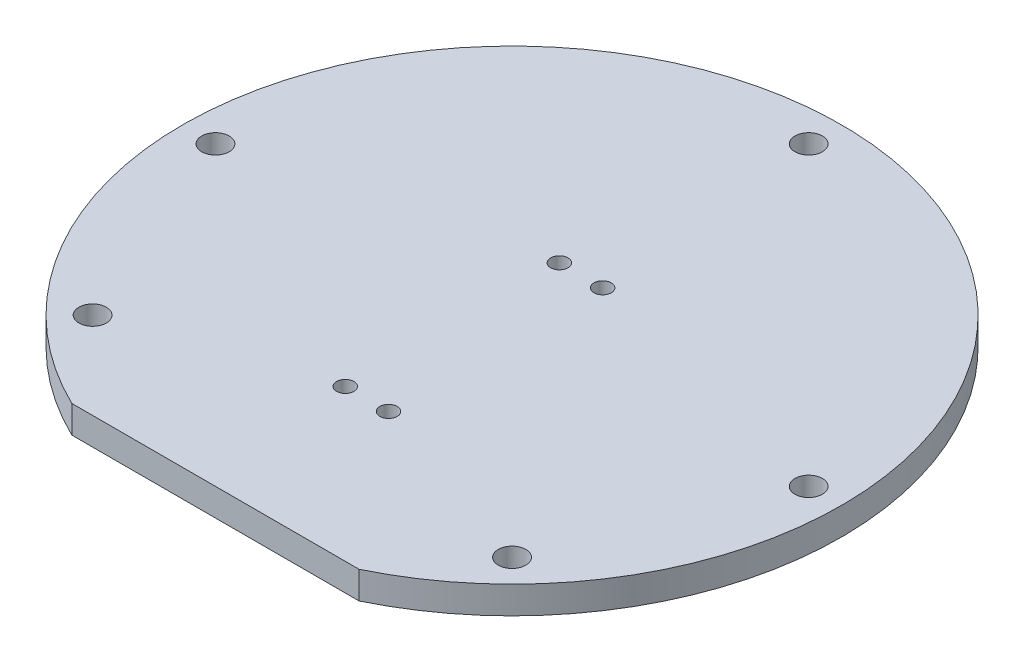
SolidWorks part; units mm, degrees
ref_plane "Front" through (0, 0, 0) normal (0, 0, 1) x (1, 0, 0)
ref_plane "Top" through (0, 0, 0) normal (0, 1, 0) x (1, 0, 0)
ref_plane "Right" through (0, 0, 0) normal (1, 0, 0) x (0, 0, -1)
sketch "Sketch1" plane through (0, 0, 0) normal (0, 1, 0) x (1, 0, 0)
  line L0 (-5.0038, 15.9411) -> (5.0038, -33.5635) construction
  line L1 (-5.0038, -33.5635) -> (5.0038, 15.9411) construction
  line L2 (33.2148, -68.58) -> (-33.2148, -68.58)
  circle A0 centre (0, 0) radius 76.2
  circle A1 centre (-5.0038, 15.9411) radius 2
  circle A2 centre (5.0038, -33.5635) radius 2
  circle A3 centre (5.0038, 15.9411) radius 2
  circle A4 centre (-5.0038, -33.5635) radius 2
  circle A5 centre (-68.58, 0) radius 3.175
  circle A6 centre (68.58, 0) radius 3.175
  circle A7 centre (0, 68.58) radius 3.175
  circle A9 centre (0, 0) radius 68.58 construction
  circle A10 centre (-48.4934, -48.4934) radius 3.175
  circle A11 centre (48.4934, -48.4934) radius 3.175
  point P16 (0, -8.8112)
  dimension "D1" = 152.4
  dimension "D2" = 33.9344
  dimension "D5" = 6.35
  dimension "D6" = 137.16
  dimension "D7" = 4
  dimension "D9" = 45
  dimension "D3" = 10.0076
  dimension "D4" = 49.5046
  dimension "D8" = 68.58
  dimension "D10" = 45
extrude "Boss-Extrude1" add sketch "Sketch1" along normal blind 6.35 contours L2 A0 A10 A7 A6 A5 A4 A3 A2 A1
